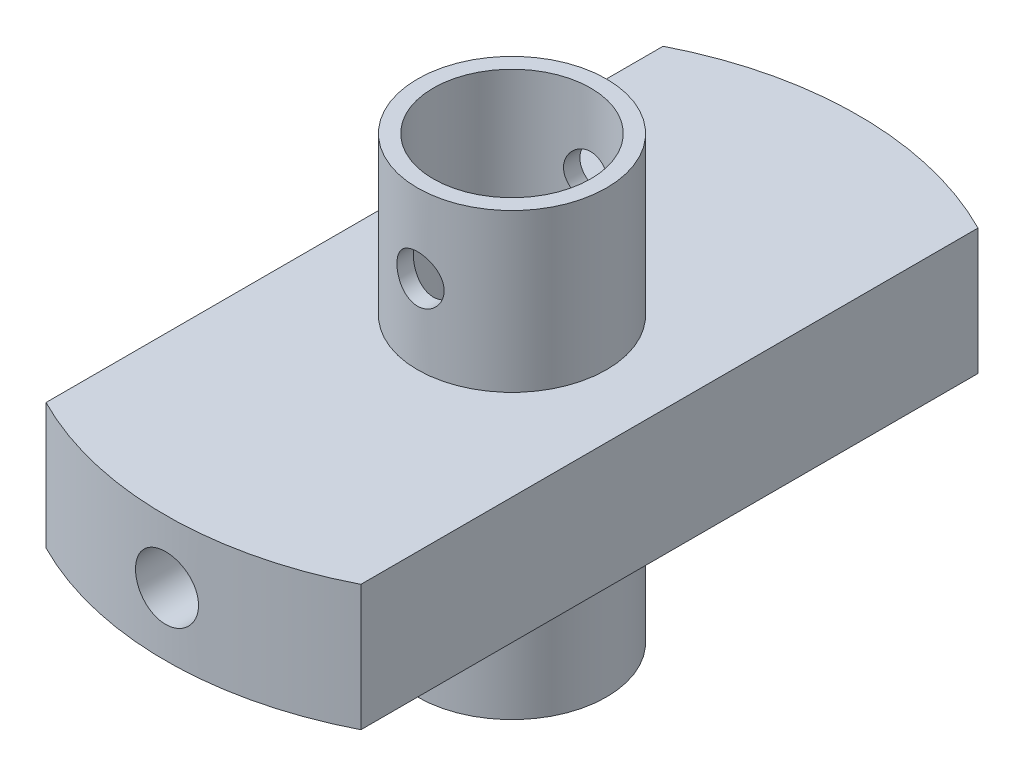
SolidWorks part; units mm, degrees
material "Delrin 2700 NC010, Low Viscosity Acetal Copolymer (SS)"
ref_plane "Front Plane" through (0, 0, 0) normal (0, 0, 1) x (1, 0, 0)
ref_plane "Top Plane" through (0, 0, 0) normal (0, 1, 0) x (1, 0, 0)
ref_plane "Right Plane" through (0, 0, 0) normal (1, 0, 0) x (0, 0, -1)
sketch "Sketch1" plane through (0, 0, 0) normal (0, 0, 1) x (1, 0, 0)
  line L0 (5, 0) -> (6, 0)
  line L1 (6, 0) -> (6, 10)
  line L2 (6, 10) -> (22, 10)
  line L3 (22, 10) -> (22, 18)
  line L4 (0, 0) -> (0, 39.5658) construction
  line L5 (5, 18) -> (22, 18)
  line L6 (5, 0) -> (5, 13)
  line L8 (5, 18) -> (5, 13)
  dimension "D1" = 18
  dimension "D2" = 10
  dimension "D3" = 12
  dimension "D4" = 8
  dimension "D5" = 44
revolve "Revolve1" add sketch "Sketch1" angle 360 about L4
sketch "Sketch2" plane through (0, 18, 0) normal (0, 1, 0) x (1, 0, 0)
  circle A0 centre (0, 0) radius 6
  circle A1 centre (0, 0) radius 5
  dimension "D1" = 12
  dimension "D2" = 10
extrude "Boss-Extrude1" add sketch "Sketch2" along normal blind 10
ref_plane "Plane1" through (0, 0, -6) normal (0, 0, -1) x (-1, 0, 0)
sketch "Sketch3" plane through (0, 0, -6) normal (0, 0, -1) x (-1, 0, 0)
  line L0 (-6, 0) -> (6, 0) construction
  line L1 (22, 18) -> (-22, 18) construction
  circle A0 centre (0, 5) radius 1.5
  circle A1 centre (0, 23) radius 1.5
  dimension "D1" = 3
  dimension "D3" = 3
  dimension "D2" = 5
  dimension "D4" = 5
extrude "Cut-Extrude1" cut sketch "Sketch3" against normal through all
sketch "Sketch4" plane through (0, 0, 0) normal (0, 0, 1) x (1, 0, 0)
  line L0 (22, 18) -> (-22, 18) construction
  circle A0 centre (0, 14) radius 2
  dimension "D1" = 4
  dimension "D2" = 4
extrude "Cut-Extrude2" cut sketch "Sketch4" against normal through all both and the other way through all
sketch "Sketch5" plane through (0, 10, 0) normal (0, -1, 0) x (1, 0, 0)
  line L0 (0, 0) -> (0, 53.0785) construction
  line L1 (-30, 22.5) -> (-10, 22.5)
  line L2 (-10, 22.5) -> (-10, -22.5)
  line L3 (-10, -22.5) -> (-30, -22.5)
  line L4 (-30, -22.5) -> (-30, 22.5)
  line L5 (30, -22.5) -> (30, 22.5)
  line L6 (10, -22.5) -> (30, -22.5)
  line L7 (10, 22.5) -> (10, -22.5)
  line L8 (30, 22.5) -> (10, 22.5)
  dimension "D1" = 20
  dimension "D2" = 10
  dimension "D3" = 45
  dimension "D4" = 22.5
extrude "Cut-Extrude3" cut sketch "Sketch5" against normal blind 10
